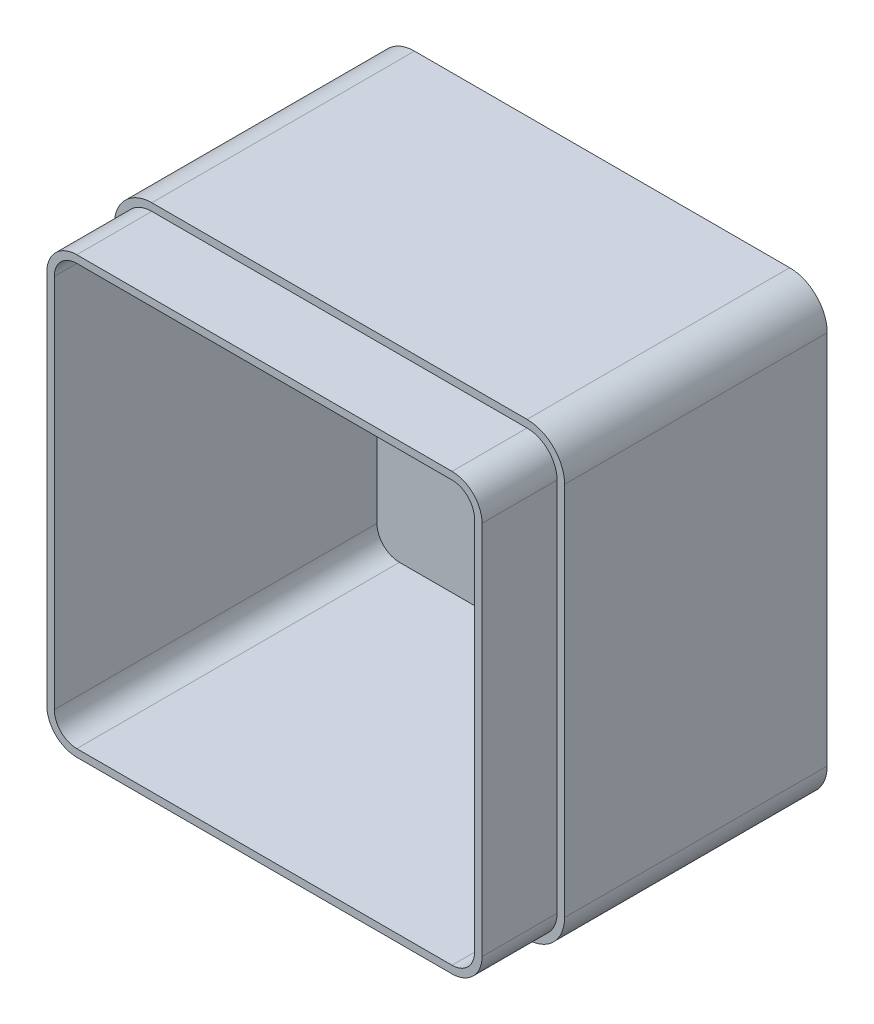
SolidWorks part; units mm, degrees
ref_plane "Front Plane" through (0, 0, 0) normal (0, 0, 1) x (1, 0, 0)
ref_plane "Top Plane" through (0, 0, 0) normal (0, 1, 0) x (1, 0, 0)
ref_plane "Right Plane" through (0, 0, 0) normal (1, 0, 0) x (0, 0, -1)
sketch "Sketch1" plane through (0, 0, 0) normal (0, 0, 1) x (1, 0, 0)
  line L1 (0, 0) -> (120, 0)
  line L2 (0, 0) -> (0, 120)
  line L3 (0, 120) -> (120, 120)
  line L4 (120, 0) -> (120, 120)
  dimension "D1" = 120
  dimension "D2" = 120
extrude "Boss-Extrude1" add sketch "Sketch1" along normal blind 90
fillet "Fillet1" radius 10 4 edges at (120, 0, 45) (0, 0, 45) (120, 120, 45) (0, 120, 45)
shell "Shell1" thickness 4
sketch "Sketch9" plane through (0, 0, 90) normal (0, 0, 1) x (1, 0, 0)
  line L4 (10, 0) -> (110, 0)
  line L5 (120, 10) -> (120, 110)
  line L6 (110, 120) -> (10, 120)
  line L7 (0, 110) -> (0, 10)
  line L8 (10, 0) -> (110, 0)
  line L9 (120, 10) -> (120, 110)
  line L10 (110, 120) -> (10, 120)
  line L11 (0, 110) -> (0, 10)
  line L17 (10, 2) -> (110, 2)
  line L18 (118, 10) -> (118, 110)
  line L19 (110, 118) -> (10, 118)
  line L20 (2, 110) -> (2, 10)
  line L21 (10, 2) -> (110, 2)
  line L22 (118, 10) -> (118, 110)
  line L23 (110, 118) -> (10, 118)
  line L24 (2, 110) -> (2, 10)
  arc A4 (110, 0) -> (120, 10) centre (110, 10) ccw
  arc A5 (120, 110) -> (110, 120) centre (110, 110) ccw
  arc A6 (10, 120) -> (0, 110) centre (10, 110) ccw
  arc A7 (0, 10) -> (10, 0) centre (10, 10) ccw
  arc A8 (110, 0) -> (120, 10) centre (110, 10) ccw
  arc A9 (120, 110) -> (110, 120) centre (110, 110) ccw
  arc A10 (10, 120) -> (0, 110) centre (10, 110) ccw
  arc A11 (0, 10) -> (10, 0) centre (10, 10) ccw
  arc A16 (110, 2) -> (118, 10) centre (110, 10) ccw
  arc A17 (118, 110) -> (110, 118) centre (110, 110) ccw
  arc A18 (10, 118) -> (2, 110) centre (10, 110) ccw
  arc A19 (2, 10) -> (10, 2) centre (10, 10) ccw
  arc A20 (110, 2) -> (118, 10) centre (110, 10) ccw
  arc A21 (118, 110) -> (110, 118) centre (110, 110) ccw
  arc A22 (10, 118) -> (2, 110) centre (10, 110) ccw
  arc A23 (2, 10) -> (10, 2) centre (10, 10) ccw
  dimension "D1" = 0
  dimension "D2" = 2
extrude "Cut-Extrude10" cut sketch "Sketch9" against normal blind 20
